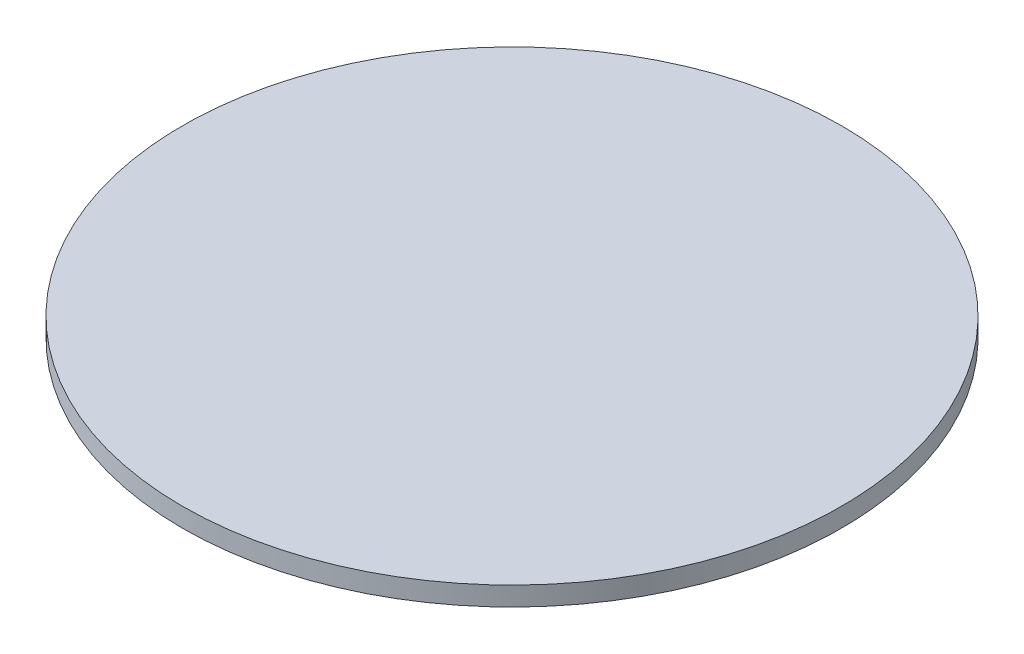
SolidWorks part; units mm, degrees
ref_plane "Front Plane" through (0, 0, 0) normal (0, 0, 1) x (1, 0, 0)
ref_plane "Top Plane" through (0, 0, 0) normal (0, 1, 0) x (1, 0, 0)
ref_plane "Right Plane" through (0, 0, 0) normal (1, 0, 0) x (0, 0, -1)
sketch "Sketch1" plane through (0, 0, 0) normal (0, 1, 0) x (1, 0, 0)
  circle A0 centre (0, 0) radius 43.9506
extrude "Boss-Extrude1" add sketch "Sketch1" along normal blind 2.54
